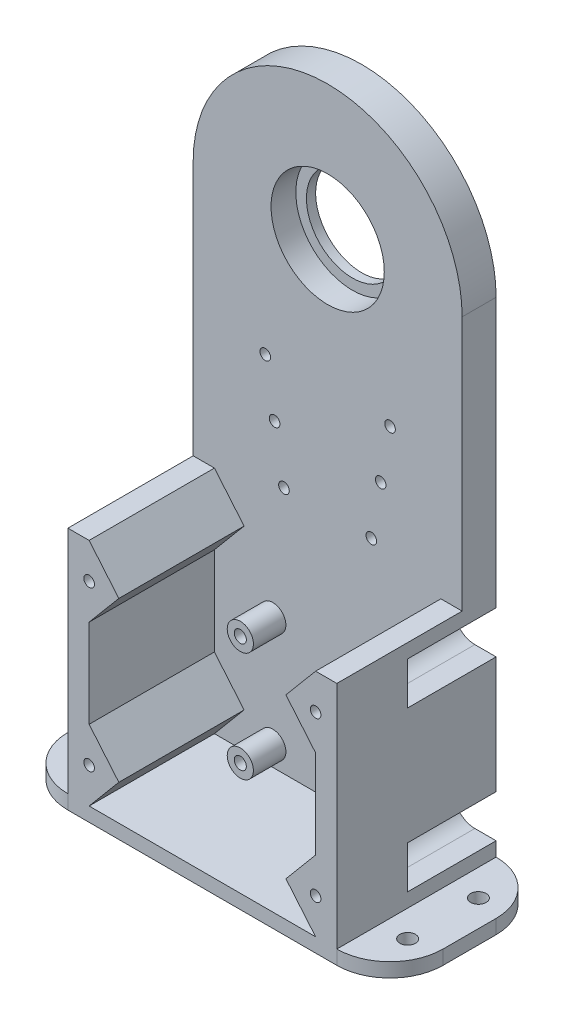
SolidWorks part; units mm, degrees
ref_plane "Ebene vorne" through (0, 0, 0) normal (0, 0, 1) x (1, 0, 0)
ref_plane "Ebene oben" through (0, 0, 0) normal (0, 1, 0) x (1, 0, 0)
ref_plane "Ebene rechts" through (0, 0, 0) normal (1, 0, 0) x (0, 0, -1)
sketch "Skizze1" plane through (0, 0, 0) normal (1, 0, 0) x (0, 0, -1)
  line L1 (-22.5, 65) -> (22.5, 65)
  line L2 (-22.5, 65) -> (-22.5, 0)
  line L3 (-22.5, 0) -> (22.5, 0)
  line L4 (22.5, 65) -> (22.5, 0)
  point P4 (0, 0)
  dimension "D1" = 45
  dimension "D2" = 65
extrude "Aufsatz-Linear austragen1" add sketch "Skizze1" along normal mid plane 76
sketch "Skizze2" plane through (0, 0, 22.5) normal (0, 0, 1) x (1, 0, 0)
  line L0 (-38, 0) -> (-32, 0)
  line L1 (38, 0) -> (-38, 0) construction
  line L2 (-32, 0) -> (-23.609, 10)
  line L3 (-23.609, 10) -> (-32, 20)
  line L4 (-32, 20) -> (-32, 45)
  line L5 (-32, 45) -> (-23.609, 55)
  line L6 (-23.609, 55) -> (-32, 65)
  line L7 (38, 65) -> (-38, 65) construction
  line L8 (-32, 65) -> (-38, 65)
  line L9 (-38, 65) -> (-38, 0)
  line L10 (-38, 32.5) -> (38, 32.5) construction
  line L11 (38, 65) -> (38, 0) construction
  line L12 (-32, 20) -> (-32, 0) construction
  line L13 (0, 0) -> (0, 65) construction
  line L14 (32, 20) -> (32, 0) construction
  line L15 (38, 65) -> (38, 0)
  line L16 (32, 65) -> (38, 65)
  line L17 (23.609, 55) -> (32, 65)
  line L18 (32, 45) -> (23.609, 55)
  line L19 (32, 20) -> (32, 45)
  line L20 (23.609, 10) -> (32, 20)
  line L21 (32, 0) -> (23.609, 10)
  line L22 (38, 0) -> (32, 0)
  point P18 (-32, 32.5)
  dimension "D1" = 25
  dimension "D2" = 100
  dimension "D3" = 6
extrude "Schnitt-Linear austragen1" cut sketch "Skizze2" against normal blind 35.4 flip side to cut
sketch "Skizze3" plane through (0, 0, -22.5) normal (0, 0, -1) x (-1, 0, 0)
  line L0 (-32, 16) -> (-38, 16)
  line L1 (-38, 0) -> (-38, 65) construction
  line L2 (-32, 4) -> (-38, 4)
  line L3 (-38, 0) -> (38, 0) construction
  line L4 (-38, 16) -> (-38, 4)
  line L5 (0, 0) -> (0, 65) construction
  line L6 (-38, 65) -> (38, 65) construction
  line L7 (-38, 32.5) -> (38, 32.5) construction
  line L8 (38, 0) -> (38, 65) construction
  line L9 (38, 16) -> (38, 4)
  line L10 (32, 4) -> (38, 4)
  line L11 (32, 16) -> (38, 16)
  line L12 (32, 49) -> (38, 49)
  line L13 (32, 61) -> (38, 61)
  line L14 (38, 49) -> (38, 61)
  line L15 (-38, 49) -> (-38, 61)
  line L16 (-32, 61) -> (-38, 61)
  line L17 (-32, 49) -> (-38, 49)
  arc A0 (-32, 4) -> (-32, 16) centre (-32, 10) ccw
  arc A1 (32, 4) -> (32, 16) centre (32, 10) cw
  arc A2 (32, 61) -> (32, 49) centre (32, 55) ccw
  arc A3 (-32, 61) -> (-32, 49) centre (-32, 55) cw
  dimension "D1" = 10
  dimension "D2" = 12
  dimension "D3" = 6
extrude "Schnitt-Linear austragen2" cut sketch "Skizze3" against normal blind 25
sketch "Skizze4" plane through (0, 0, 2.5) normal (0, 0, -1) x (-1, 0, 0)
  line L0 (0, 0) -> (0, 65) construction
  line L1 (-38, 0) -> (38, 0) construction
  line L2 (-38, 65) -> (38, 65) construction
  line L3 (-38, 32.5) -> (38, 32.5) construction
  line L4 (-38, 16) -> (-38, 49) construction
  line L5 (38, 16) -> (38, 49) construction
  circle A0 centre (32, 10) radius 1.5
  circle A1 centre (-32, 10) radius 1.5
  circle A2 centre (-32, 55) radius 1.5
  circle A3 centre (32, 55) radius 1.5
  dimension "D1" = 3
extrude "Schnitt-Linear austragen3" cut sketch "Skizze4" against normal through all
sketch "Skizze5" plane through (0, 0, -12.9) normal (0, 0, 1) x (1, 0, 0)
  line L0 (-38, 65) -> (38, 65)
  line L1 (38, 65) -> (38, 137)
  line L2 (-38, 137) -> (-38, 65)
  arc A0 (38, 137) -> (-38, 137) centre (0, 137) ccw
  dimension "D1" = 110
extrude "Aufsatz-Linear austragen2" add sketch "Skizze5" against normal up to surface (9.6 mm away) up to face at (0, 32.5, -22.5)
sketch "Skizze6" plane through (0, 0, -12.9) normal (0, 0, 1) x (1, 0, 0)
  circle A0 centre (0, 137) radius 16
  dimension "D1" = 32
extrude "Schnitt-Linear austragen4" cut sketch "Skizze6" against normal blind 7
sketch "Skizze8" plane through (0, 0, -22.5) normal (0, 0, -1) x (-1, 0, 0)
  circle A0 centre (0, 137) radius 13
  dimension "D1" = 26
extrude "Schnitt-Linear austragen5" cut sketch "Skizze8" against normal through all
sketch "Skizze9" plane through (0, 0, -22.5) normal (0, 0, -1) x (-1, 0, 0)
  line L0 (0, 0) -> (28.5739, 162.0506) construction
  line L1 (-38, 0) -> (38, 0) construction
  line L2 (0, 0) -> (0, 175) construction
  arc A0 (38, 137) -> (-38, 137) centre (0, 137) ccw construction
  circle A1 centre (12.3429, 70) radius 1.5
  circle A2 centre (14.9878, 85) radius 1.5
  circle A3 centre (17.6327, 100) radius 1.5
  circle A4 centre (-12.3429, 70) radius 1.5
  circle A5 centre (-17.6327, 100) radius 1.5
  circle A6 centre (-14.9878, 85) radius 1.5
  dimension "D2" = 3
  dimension "D1" = 100
  dimension "D3" = 70
  dimension "D4" = 15
  dimension "D5" = 15
extrude "Schnitt-Linear austragen6" cut sketch "Skizze9" against normal through all
sketch "Skizze12" plane through (0, 0, 0) normal (0, -1, 0) x (1, 0, 0)
  line L1 (-38, 22.5) -> (38, 22.5)
  line L2 (-38, 22.5) -> (-38, -22.5)
  line L3 (-38, -22.5) -> (38, -22.5)
  line L4 (38, 22.5) -> (38, -22.5)
extrude "Aufsatz-Linear austragen4" add sketch "Skizze12" along normal blind 4
sketch "Skizze10" plane through (38, 0, 0) normal (1, 0, 0) x (0, 0, -1)
  line L0 (-22.5, 65) -> (-22.5, -4) construction
  line L1 (22.5, -4) -> (-22.5, -4)
  line L2 (22.5, -4) -> (22.5, 0)
  line L3 (22.5, 0) -> (-22.5, 0)
  line L4 (-22.5, -4) -> (-22.5, 0)
  line L5 (22.5, -4) -> (22.5, 4) construction
  line L7 (22.5, -4) -> (-22.5, -4) construction
  point P6 (22.5, 0)
  point P8 (22.5, 3.1403)
  dimension "D1" = 4
extrude "Aufsatz-Linear austragen3" add sketch "Skizze10" along normal blind 15
fillet "Verrundung1" radius 15 2 edges at (53, -2, 22.5) (53, -2, -22.5)
sketch "Skizze11" plane through (0, 4, 0) normal (0, 1, 0) x (1, 0, 0)
  line L0 (53, 0) -> (38, 0) construction
  line L1 (53, 7.5) -> (53, -7.5) construction
  line L2 (38, 12.9) -> (38, -22.5) construction
  line L3 (45.5, 0) -> (45.5, 10) construction
  circle A0 centre (45.5, 10) radius 2.2
  circle A1 centre (45.5, -10) radius 2.2
  point P11 (45.9954, 11.7434)
  dimension "D1" = 4.4
  dimension "D2" = 10
extrude "Schnitt-Linear austragen7" cut sketch "Skizze11" against normal through all
mirror "Spiegeln1" about plane through (0, 0, 0) normal (1, 0, 0) of "Schnitt-Linear austragen7", "Verrundung1", "Aufsatz-Linear austragen3"
sketch "Skizze13" plane through (0, 0, -12.9) normal (0, 0, 1) x (1, 0, 0)
  line L0 (0, 0) -> (0, 42.3) construction
  line L1 (-9.8972, 21.15) -> (11.2382, 21.15) construction
  circle A0 centre (-15.5, 36.65) radius 1.7
  circle A1 centre (-15.5, 36.65) radius 3.7
  circle A3 centre (15.5, 36.65) radius 1.7
  circle A4 centre (15.5, 36.65) radius 3.7
  circle A5 centre (15.5, 5.65) radius 1.7
  circle A6 centre (15.5, 5.65) radius 3.7
  circle A7 centre (-15.5, 5.65) radius 1.7
  circle A8 centre (-15.5, 5.65) radius 3.7
  point P5 (0.6705, 21.15)
  point P6 (0, 21.15)
  point P10 (0, 21.15)
  point P24 (0, 21.15)
  dimension "D2" = 31
  dimension "D3" = 31
  dimension "D4" = 3.4
  dimension "D5" = 2
  dimension "D6" = 4
  dimension "D1" = 42.3
extrude "Aufsatz-Linear austragen5" add sketch "Skizze13" along normal up to surface (9.1787 mm away)
chamfer "Fase1" [suppressed] distance 3 angle 60
sketch "Skizze14" plane through (0, 0, -12.9) normal (0, 0, 1) x (1, 0, 0)
  circle A0 centre (-15.5, 5.65) radius 1.7 construction
  circle A1 centre (15.5, 5.65) radius 1.7 construction
  circle A2 centre (15.5, 36.65) radius 1.7 construction
  circle A3 centre (-15.5, 36.65) radius 1.7 construction
  circle A4 centre (-15.5, 5.65) radius 1.7
  circle A5 centre (15.5, 5.65) radius 1.7
  circle A6 centre (15.5, 36.65) radius 1.7
  circle A7 centre (-15.5, 36.65) radius 1.7
extrude "Schnitt-Linear austragen8" cut sketch "Skizze14" against normal up to surface (9.6 mm away) up to face at (-14.9878, 86.5, -22.5)
sketch "Skizze15" plane through (0, 0, -22.5) normal (0, 0, -1) x (-1, 0, 0)
  circle A0 centre (0, 21.15) radius 5
  dimension "D1" = 10
extrude "Schnitt-Linear austragen9" cut sketch "Skizze15" against normal up to surface (9.6 mm away) up to face at (-11.8, 5.65, -12.9)
